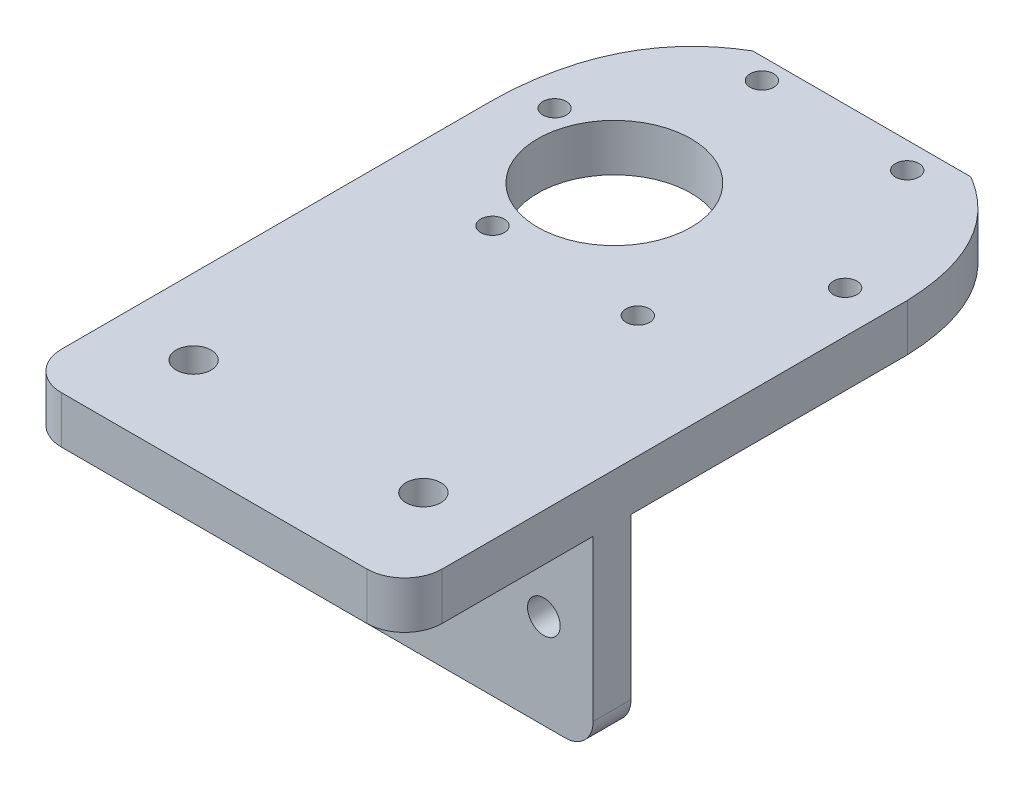
SolidWorks part; units mm, degrees
ref_plane "Front Plane" through (0, 0, 0) normal (0, 0, 1) x (1, 0, 0)
ref_plane "Top Plane" through (0, 0, 0) normal (0, 1, 0) x (1, 0, 0)
ref_plane "Right Plane" through (0, 0, 0) normal (1, 0, 0) x (0, 0, -1)
sketch "Sketch1" plane through (0, 0, 0) normal (0, 0, 1) x (1, 0, 0)
  line L1 (44.1412, -69.433) -> (9.7912, -69.433)
  line L6 (14.3097, -56.5937) -> (14.3097, -62.2724) construction
  line L8 (47.1412, -56.5937) -> (-277.8588, -56.5937) construction
  line L13 (47.1412, -66.433) -> (47.1412, -12.433)
  line L14 (42.1412, -7.433) -> (11.7912, -7.433)
  line L15 (6.7912, -12.433) -> (6.7912, -66.433)
  line L27 (47.1412, -62.2724) -> (-277.8588, -62.2724) construction
  circle A2 centre (12.0212, -14.663) radius 1.73
  circle A3 centre (41.9112, -14.663) radius 1.73
  arc A9 (47.1412, -12.433) -> (42.1412, -7.433) centre (42.1412, -12.433) ccw
  arc A10 (11.7912, -7.433) -> (6.7912, -12.433) centre (11.7912, -12.433) ccw
  circle A12 centre (12.0212, -38.723) radius 1.75
  circle A13 centre (41.9112, -38.723) radius 1.75
  arc A14 (6.7912, -66.433) -> (9.7912, -69.433) centre (9.7912, -66.433) ccw
  arc A15 (47.1412, -66.433) -> (44.1412, -69.433) centre (44.1412, -66.433) cw
  circle A16 centre (41.9112, -59.433) radius 1.73
  circle A17 centre (12.0212, -59.433) radius 1.73
  point P1 (0, 0)
  point P2 (14.3097, -59.433)
  dimension "D2" = 3.5
  dimension "D3" = 3.5
  dimension "D4" = 3
  dimension "D6" = 31.29
  dimension "D1" = 7.23
  dimension "D5" = 31.29
extrude "Boss-Extrude1" add sketch "Sketch1" along normal blind 4
sketch "Sketch2" plane through (0, 0, 4) normal (0, 0, 1) x (1, 0, 0)
  line L3 (47.1412, -49.433) -> (47.1412, -44.433)
  line L4 (6.7912, -44.433) -> (6.7912, -49.433)
  line L5 (47.1412, -49.433) -> (6.7912, -49.433)
  line L6 (47.1412, -44.433) -> (6.7912, -44.433)
  dimension "D1" = 5
extrude "Boss-Extrude2" add sketch "Sketch2" along normal blind 20
fillet "Fillet1" radius 4 2 edges at (47.1412, -46.933, 24) (6.7912, -46.933, 24)
sketch "Sketch3" plane through (0, -44.433, 0) normal (0, 1, 0) x (1, 0, 0)
  line L0 (47.1412, -20) -> (47.1412, -4) construction
  line L1 (47.3884, -14) -> (42.4961, -14) construction
  line L2 (6.7912, -20) -> (6.7912, -4) construction
  circle A0 centre (39.1412, -14) radius 1.85
  circle A1 centre (14.7912, -14) radius 1.85
  dimension "D1" = 3.7
  dimension "D2" = 3.7
  dimension "D3" = 8
  dimension "D4" = 8
extrude "Cut-Extrude1" cut sketch "Sketch3" against normal through all
sketch "Sketch4" plane through (0, 0, 4) normal (0, 0, 1) x (1, 0, 0)
  line L1 (6.7912, -44.433) -> (49.1263, -44.433)
  line L2 (6.7912, -44.433) -> (6.7912, -3.8984)
  line L3 (6.7912, -3.8984) -> (49.1263, -3.8984)
  line L4 (49.1263, -44.433) -> (49.1263, -3.8984)
extrude "Cut-Extrude2" cut sketch "Sketch4" against normal through all
sketch "Sketch5" plane through (0, 0, 0) normal (0, 0, -1) x (-1, 0, 0)
  line L0 (-6.7912, -44.433) -> (-6.7912, -66.433) construction
  line L1 (-47.1412, -66.433) -> (-47.1412, -44.433) construction
  line L2 (-6.7912, -44.433) -> (-47.1412, -44.433) construction
  line L3 (-6.7912, -49.433) -> (-47.1412, -49.433) construction
  line L4 (-6.7912, -44.433) -> (-6.7912, -49.433)
  line L5 (-47.1412, -49.433) -> (-47.1412, -44.433)
  line L6 (-6.7912, -44.433) -> (-47.1412, -44.433)
  line L7 (-6.7912, -49.433) -> (-47.1412, -49.433)
extrude "Boss-Extrude3" add sketch "Sketch5" along normal blind 44
sketch "Sketch7" plane through (0, -49.433, 0) normal (0, -1, 0) x (1, 0, 0)
  line L0 (6.7912, -44) -> (6.7912, 0) construction
  line L2 (47.1412, 24) -> (47.1412, -226) construction
  line L3 (6.7912, -24.6807) -> (4.5826, -44)
  line L4 (4.5826, -44) -> (32.6773, -51.0003)
  line L5 (32.6773, -51.0003) -> (44.9451, -48.6142)
  line L6 (44.9451, -48.6142) -> (51.5498, -38.8199)
  line L7 (51.5498, -38.8199) -> (47.1412, -27.1903)
  circle A0 centre (20.8367, -24.5453) radius 8.1328
  circle A1 centre (18.3091, -14.1623) radius 1.25
  circle A2 centre (18.3091, -14.1623) radius 1.25
  circle A3 centre (10.809, -28.2389) radius 1.25
  circle A4 centre (10.809, -28.2389) radius 1.25
  circle A5 centre (19.2496, -41.7725) radius 1.25
  circle A6 centre (19.2496, -41.7725) radius 1.25
  circle A7 centre (35.1903, -41.2295) radius 1.25
  circle A8 centre (35.1903, -41.2295) radius 1.25
  circle A9 centre (42.6905, -27.1529) radius 1.25
  circle A10 centre (42.6905, -27.1529) radius 1.25
  circle A11 centre (34.2498, -13.6193) radius 1.25
  circle A12 centre (34.2498, -13.6193) radius 1.25
  spline S0 degree 2 poles (6.7912, -24.6807) (6.595, -44.8679) (26.7497, -47.3243) knots 0 0 0 1 1 1
  spline S1 degree 2 poles (26.7497, -47.3243) (47.7707, -45.8748) (47.1412, -27.1903) knots 0 0 0 1 1 1
  point P26 (26.7497, -47.3243)
  point P36 (11.5552, -40.2889)
  point P37 (44.5442, -38.8199)
  point P38 (0, 0)
  dimension "D1" = 0
  dimension "D2" = 0
  dimension "D3" = 0
  dimension "D4" = 0
  dimension "D5" = 0
  dimension "D6" = 0
extrude "Cut-Extrude3" cut sketch "Sketch7" against normal blind 10
